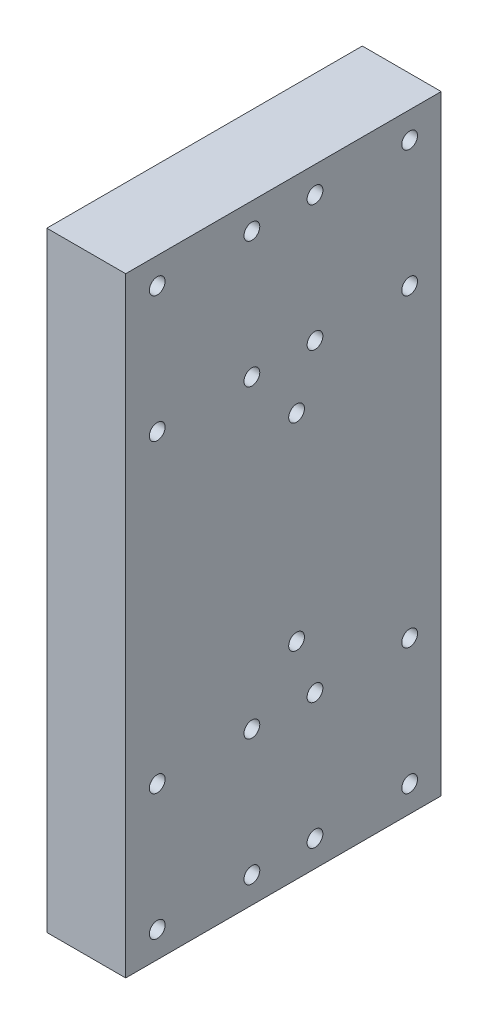
SolidWorks part; units mm, degrees
ref_plane "Alzado" through (0, 0, 0) normal (0, 0, 1) x (1, 0, 0)
ref_plane "Planta" through (0, 0, 0) normal (0, 1, 0) x (1, 0, 0)
ref_plane "Vista lateral" through (0, 0, 0) normal (1, 0, 0) x (0, 0, -1)
sketch "Croquis1" plane through (0, 0, 0) normal (1, 0, 0) x (0, 0, -1)
  line L0 (30, 116) -> (30, 0) construction
  line L1 (0, 0) -> (60, 0)
  line L2 (0, 0) -> (0, 116)
  line L3 (0, 116) -> (60, 116)
  line L4 (60, 0) -> (60, 116)
  line L5 (0, 58) -> (60, 58) construction
  line L6 (32.5, 39.2) -> (32.5, 58) construction
  line L7 (32.5, 58) -> (32.5, 76.8) construction
  circle A0 centre (54, 5) radius 1.5
  circle A1 centre (36, 5) radius 1.5
  circle A2 centre (36, 29) radius 1.5
  circle A3 centre (54, 29) radius 1.5
  circle A4 centre (24, 29) radius 1.5
  circle A5 centre (24, 5) radius 1.5
  circle A6 centre (6, 5) radius 1.5
  circle A7 centre (6, 29) radius 1.5
  circle A8 centre (6, 87) radius 1.5
  circle A9 centre (6, 111) radius 1.5
  circle A10 centre (24, 111) radius 1.5
  circle A11 centre (24, 87) radius 1.5
  circle A12 centre (36, 87) radius 1.5
  circle A13 centre (36, 111) radius 1.5
  circle A14 centre (54, 111) radius 1.5
  circle A15 centre (54, 87) radius 1.5
  circle A16 centre (32.5, 76.8) radius 1.5
  circle A17 centre (32.5, 39.2) radius 1.5
  dimension "D3" = 3
  dimension "D8" = 3
  dimension "D1" = 116
  dimension "D2" = 60
  dimension "D4" = 5
  dimension "D5" = 6
  dimension "D6" = 24
  dimension "D7" = 18
  dimension "D9" = 2.5
  dimension "D10" = 37.6
extrude "Saliente-Extruir1" add sketch "Croquis1" along normal blind 15
